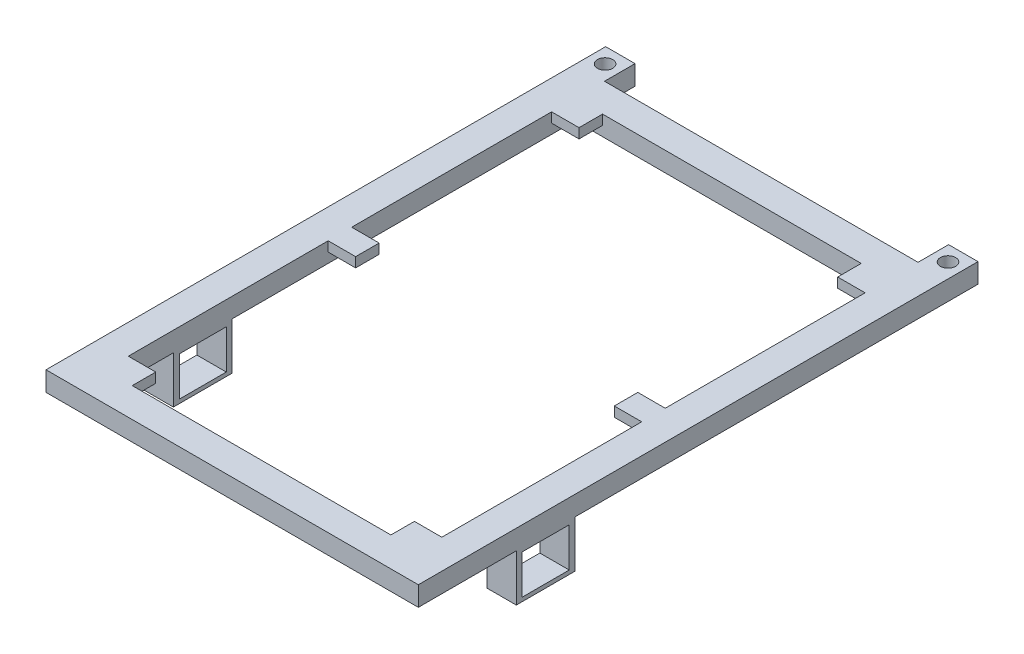
SolidWorks part; units mm, degrees
ref_plane "Front Plane" through (0, 0, 0) normal (0, 0, 1) x (1, 0, 0)
ref_plane "Top Plane" through (0, 0, 0) normal (0, 1, 0) x (1, 0, 0)
ref_plane "Right Plane" through (0, 0, 0) normal (1, 0, 0) x (0, 0, -1)
sketch "Sketch1" plane through (0, 0, 0) normal (0, 1, 0) x (1, 0, 0)
  line L1 (-62.8272, 58.7435) -> (32.1728, 58.7435)
  line L2 (-62.8272, 58.7435) -> (-62.8272, -76.2565)
  line L3 (-62.8272, -76.2565) -> (32.1728, -76.2565)
  line L4 (32.1728, 58.7435) -> (32.1728, -76.2565)
  dimension "D1" = 135
  dimension "D2" = 95
extrude "Boss-Extrude1" add sketch "Sketch1" along normal blind 5
sketch "Sketch3" plane through (0, 5, 0) normal (0, 1, 0) x (1, 0, 0)
  line L5 (-55.3272, 51.2435) -> (24.6728, 51.2435)
  line L6 (-55.3272, 51.2435) -> (-55.3272, -68.7565)
  line L7 (-55.3272, -68.7565) -> (24.6728, -68.7565)
  line L8 (24.6728, 51.2435) -> (24.6728, -68.7565)
  line L12 (32.1728, 58.7435) -> (-62.8272, 58.7435) construction
  dimension "D1" = 80
  dimension "D2" = 120
  dimension "D3" = 7.5
extrude "Cut-Extrude1" cut sketch "Sketch3" against normal through all
sketch "Sketch4" plane through (0, 5, 0) normal (0, 1, 0) x (1, 0, 0)
  line L1 (-55.3272, 51.2435) -> (-48.3272, 51.2435)
  line L2 (-55.3272, 51.2435) -> (-55.3272, 45.2435)
  line L3 (-55.3272, 45.2435) -> (-48.3272, 45.2435)
  line L4 (-48.3272, 51.2435) -> (-48.3272, 45.2435)
  line L8 (17.6728, -62.7565) -> (24.6728, -62.7565)
  line L9 (17.6728, 51.2435) -> (24.6728, 51.2435)
  line L10 (17.6728, 51.2435) -> (17.6728, 45.2435)
  line L11 (17.6728, 45.2435) -> (24.6728, 45.2435)
  line L12 (24.6728, 51.2435) -> (24.6728, 45.2435)
  line L13 (24.6728, 51.2435) -> (-55.3272, 51.2435) construction
  line L14 (24.6728, -68.7565) -> (24.6728, 51.2435) construction
  line L15 (-55.3272, -62.7565) -> (-48.3272, -62.7565)
  line L16 (-55.3272, -62.7565) -> (-55.3272, -68.7565)
  line L17 (-55.3272, -68.7565) -> (-48.3272, -68.7565)
  line L18 (-48.3272, -62.7565) -> (-48.3272, -68.7565)
  line L19 (-55.3272, -68.7565) -> (24.6728, -68.7565) construction
  line L20 (-55.3272, 51.2435) -> (-55.3272, -68.7565) construction
  line L25 (17.6728, -62.7565) -> (17.6728, -68.7565)
  line L26 (17.6728, -68.7565) -> (24.6728, -68.7565)
  line L27 (24.6728, -62.7565) -> (24.6728, -68.7565)
  line L28 (24.6728, -8.7565) -> (17.6728, -8.7565)
  line L29 (17.6728, -8.7565) -> (17.6728, -5.7565)
  line L30 (17.6728, -5.7565) -> (24.6728, -5.7565)
  line L31 (17.6728, -8.7565) -> (17.6728, -11.7565)
  line L32 (17.6728, -11.7565) -> (24.6728, -11.7565)
  line L34 (-55.3272, -5.7565) -> (-48.3272, -5.7565)
  line L35 (-55.3272, -5.7565) -> (-55.3272, -11.7565)
  line L36 (-55.3272, -11.7565) -> (-48.3272, -11.7565)
  line L37 (-48.3272, -5.7565) -> (-48.3272, -11.7565)
  line L38 (17.6728, -5.7565) -> (24.6728, -5.7565)
  line L39 (17.6728, -5.7565) -> (17.6728, -11.7565)
  line L40 (17.6728, -11.7565) -> (24.6728, -11.7565)
  line L41 (24.6728, -5.7565) -> (24.6728, -11.7565)
  dimension "D1" = 7
  dimension "D2" = 6
  dimension "D3" = 0
  dimension "D4" = 0
  dimension "D5" = 6
  dimension "D6" = 7
  dimension "D7" = 0
  dimension "D8" = 0
  dimension "D9" = 7
  dimension "D10" = 6
  dimension "D11" = 0
  dimension "D12" = 0
  dimension "D13" = 6
  dimension "D14" = 7
  dimension "D15" = 3
  dimension "D16" = 3
extrude "Boss-Extrude4" add sketch "Sketch4" against normal blind 2.5 contours L2 L1 L4 L3 | L35 L34 L37 L36 | L15 L18 L17 L16 | L8 L27 L26 L25 | L39 L38 L41 L40 | L9 L12 L11 L10
sketch "Sketch6" plane through (0, 0, 0) normal (0, -1, 0) x (1, 0, 0)
  line L0 (24.6728, -58.7435) -> (32.1728, -58.7435)
  line L1 (-62.8272, -58.7435) -> (-55.3272, -58.7435)
  line L2 (-62.8272, -58.7435) -> (-62.8272, -66.5435)
  line L3 (-62.8272, -66.5435) -> (-55.3272, -66.5435)
  line L4 (-55.3272, -58.7435) -> (-55.3272, -66.5435)
  line L5 (24.6728, -58.7435) -> (24.6728, -66.5435)
  line L6 (24.6728, -66.5435) -> (32.1728, -66.5435)
  line L7 (32.1728, -58.7435) -> (32.1728, -66.5435)
  point P12 (32.7565, -58.8626)
  point P13 (33.0465, -58.634)
  point P15 (34.6915, -68.4032)
  dimension "D1" = 7.8
  dimension "D2" = 7.5
  dimension "D3" = 0
  dimension "D4" = 7.5
  dimension "D5" = 7.8
extrude "Boss-Extrude5" add sketch "Sketch6" against normal blind 5
sketch "Sketch7" plane through (0, 0, 0) normal (0, -1, 0) x (-1, 0, 0)
  circle A0 centre (59.0772, 62.6435) radius 1.95
  circle A1 centre (-28.4228, 62.6435) radius 1.95
extrude "Cut-Extrude2" cut sketch "Sketch7" against normal blind 10
sketch "Sketch16" plane through (0, 0, 0) normal (0, -1, 0) x (-1, 0, 0)
  line L0 (55.3272, 51.2435) -> (55.3272, -68.7565) construction
  line L5 (62.8272, -51.2565) -> (55.3272, -51.2565)
  line L6 (62.8272, -51.2565) -> (62.8272, -36.2565)
  line L7 (62.8272, -36.2565) -> (55.3272, -36.2565)
  line L9 (62.8272, 66.5435) -> (62.8272, -76.2565) construction
  line L10 (55.3272, -51.2565) -> (55.3272, -36.2565)
  line L11 (-24.6728, -68.7565) -> (-24.6728, 51.2435) construction
  line L12 (-24.6728, -51.2565) -> (-32.1728, -51.2565)
  line L13 (-24.6728, -51.2565) -> (-24.6728, -36.2565)
  line L14 (-24.6728, -36.2565) -> (-32.1728, -36.2565)
  line L15 (-32.1728, -51.2565) -> (-32.1728, -36.2565)
  line L16 (-32.1728, -76.2565) -> (-32.1728, 66.5435) construction
extrude "Boss-Extrude9" add sketch "Sketch16" along normal blind 12
sketch "Sketch18" plane through (-62.8272, 0, 0) normal (-1, 0, 0) x (0, 0, 1)
  line L5 (37.7565, -1) -> (49.7565, -1)
  line L6 (37.7565, -1) -> (37.7565, -11)
  line L7 (37.7565, -11) -> (49.7565, -11)
  line L8 (49.7565, -1) -> (49.7565, -11)
extrude "Cut-Extrude3" cut sketch "Sketch18" against normal blind 1002
